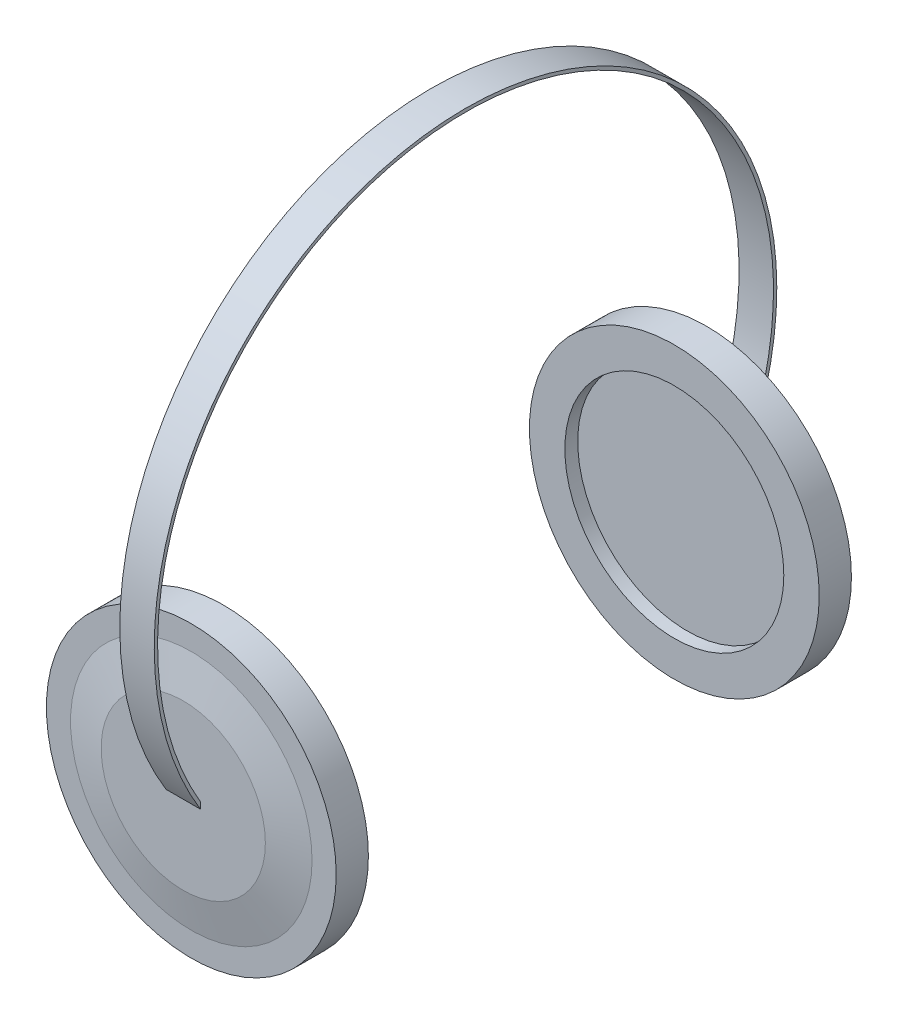
SolidWorks part; units mm, degrees
ref_plane "前视基准面" through (0, 0, 0) normal (0, 0, 1) x (1, 0, 0)
ref_plane "上视基准面" through (0, 0, 0) normal (0, 1, 0) x (1, 0, 0)
ref_plane "右视基准面" through (0, 0, 0) normal (1, 0, 0) x (0, 0, -1)
sketch "草图1" plane through (0, 0, 0) normal (0, 0, 1) x (1, 0, 0)
  line L0 (0, 0) -> (93.6964, 0) construction
  line L1 (0, 0) -> (0, -65.2385) construction
  circle A0 centre (0, 0) radius 90
extrude "凸台-拉伸1" add sketch "草图1" along normal blind 20
ref_plane "基准面1" through (0, 0, 300) normal (0, 0, 1) x (1, 0, 0)
sketch "草图2" plane through (0, 0, 300) normal (0, 0, 1) x (1, 0, 0)
  circle A0 centre (0, 0) radius 90
extrude "凸台-拉伸2" add sketch "草图2" along normal blind 20 separate body
sketch "草图3" plane through (0, 0, 300) normal (0, 0, -1) x (-1, 0, 0)
  circle A0 centre (0, 0) radius 68
extrude "切除-拉伸1" cut sketch "草图3" against normal blind 8
sketch "草图4" plane through (0, 0, 20) normal (0, 0, 1) x (1, 0, 0)
  circle A0 centre (0, 0) radius 68
extrude "切除-拉伸2" cut sketch "草图4" against normal blind 8
sketch "草图5" plane through (0, 0, 320) normal (0, 0, 1) x (1, 0, 0)
  circle A0 centre (0, 0) radius 75
ref_plane "基准面2" through (0, 0, 325) normal (0, 0, 1) x (1, 0, 0)
sketch "草图7" plane through (0, 0, 325) normal (0, 0, 1) x (1, 0, 0)
  circle A0 centre (0, 0) radius 51
loft "放样1" add profiles "草图5", "草图7"
sketch "草图8" plane through (0, 0, 0) normal (0, 0, -1) x (-1, 0, 0)
  circle A0 centre (0, 0) radius 75
ref_plane "基准面3" through (0, 0, 300) normal (0, 0, -1) x (-1, 0, 0)
ref_plane "基准面4" through (0, 0, -5) normal (0, 0, -1) x (-1, 0, 0)
sketch "草图9" plane through (0, 0, -5) normal (0, 0, -1) x (-1, 0, 0)
  circle A0 centre (0, 0) radius 51
loft "放样2" add profiles "草图8", "草图9"
sketch "草图11" plane through (0, 0, 325) normal (0, 0, 1) x (1, 0, 0)
  line L0 (0, -99) -> (0, 99) construction
  line L1 (-10.6941, 1.9896) -> (10.6941, 1.9896)
  line L2 (-10.6941, 1.9896) -> (-10.6941, -1.9896)
  line L3 (-10.6941, -1.9896) -> (10.6941, -1.9896)
  line L4 (10.6941, 1.9896) -> (10.6941, -1.9896)
  line L5 (-10.6941, 1.9896) -> (10.6941, -1.9896) construction
  line L6 (-10.6941, -1.9896) -> (10.6941, 1.9896) construction
  point P0 (0, 0)
sketch "草图14" plane through (0, 0, 0) normal (1, 0, 0) x (0, 0, -1)
  line L0 (-160.3732, 99.3761) -> (-160.3732, -134.5355) construction
  line L1 (-300, 0) -> (-20, 0) construction
  line L2 (-300, -90) -> (-300, 90) construction
  line L3 (-20, 90) -> (-20, -90) construction
  arc A0 (-5.5415, -14.4098) -> (-315.2049, -14.4098) centre (-160.3732, 99.3761) ccw
sweep "扫描1" add profiles "草图11" path "草图14"
